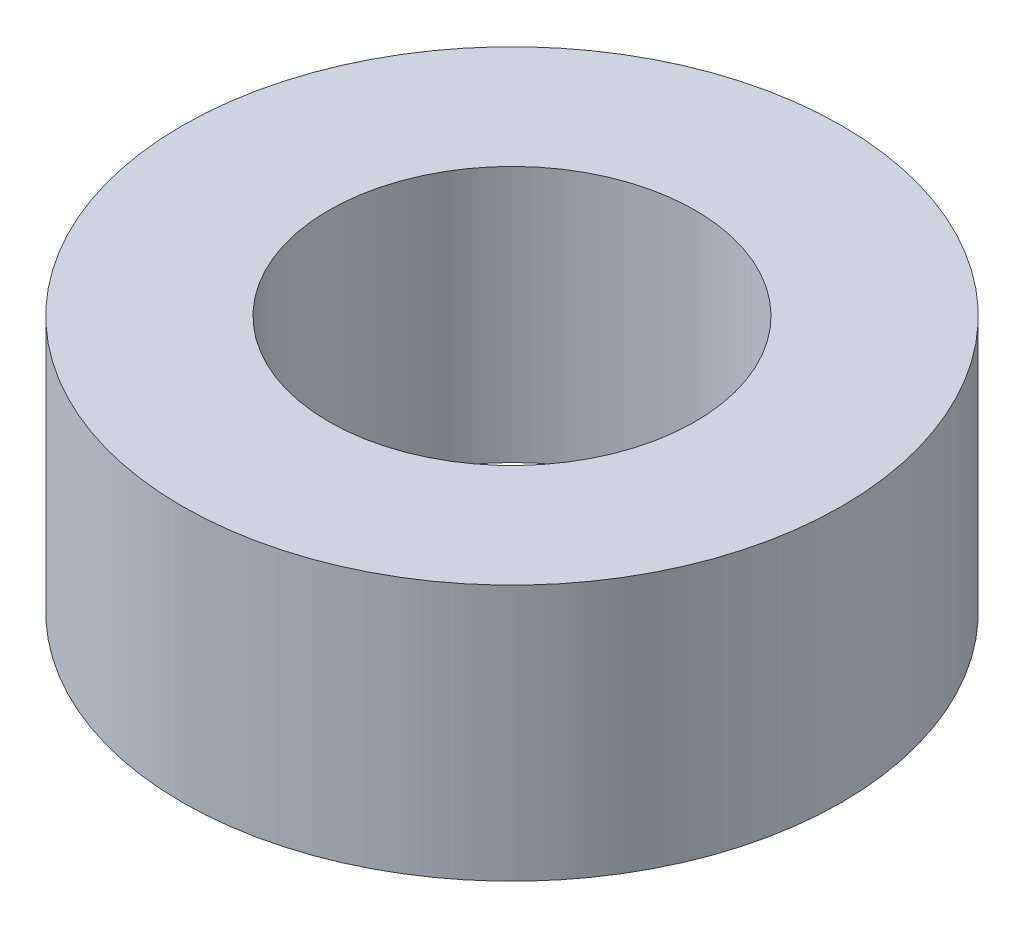
SolidWorks part; units mm, degrees
ref_plane "Front" through (0, 0, 0) normal (0, 0, 1) x (1, 0, 0)
ref_plane "Top" through (0, 0, 0) normal (0, 1, 0) x (1, 0, 0)
ref_plane "Right" through (0, 0, 0) normal (1, 0, 0) x (0, 0, -1)
sketch "Sketch1" plane through (0, 0, 0) normal (1, 0, 0) x (0, 0, -1)
  line L0 (0, 5.423) -> (0, 0) construction
  line L1 (0, 0) -> (5.6595, 0) construction
  line L3 (2.5, 1.75) -> (4.5, 1.75)
  line L4 (2.5, 1.75) -> (2.5, -1.75)
  line L5 (2.5, -1.75) -> (4.5, -1.75)
  line L6 (4.5, 1.75) -> (4.5, -1.75)
  dimension "D1" = 5
  dimension "D2" = 9
  dimension "D3" = 3.5
revolve "Revolve1" add sketch "Sketch1" angle 360 about L0
